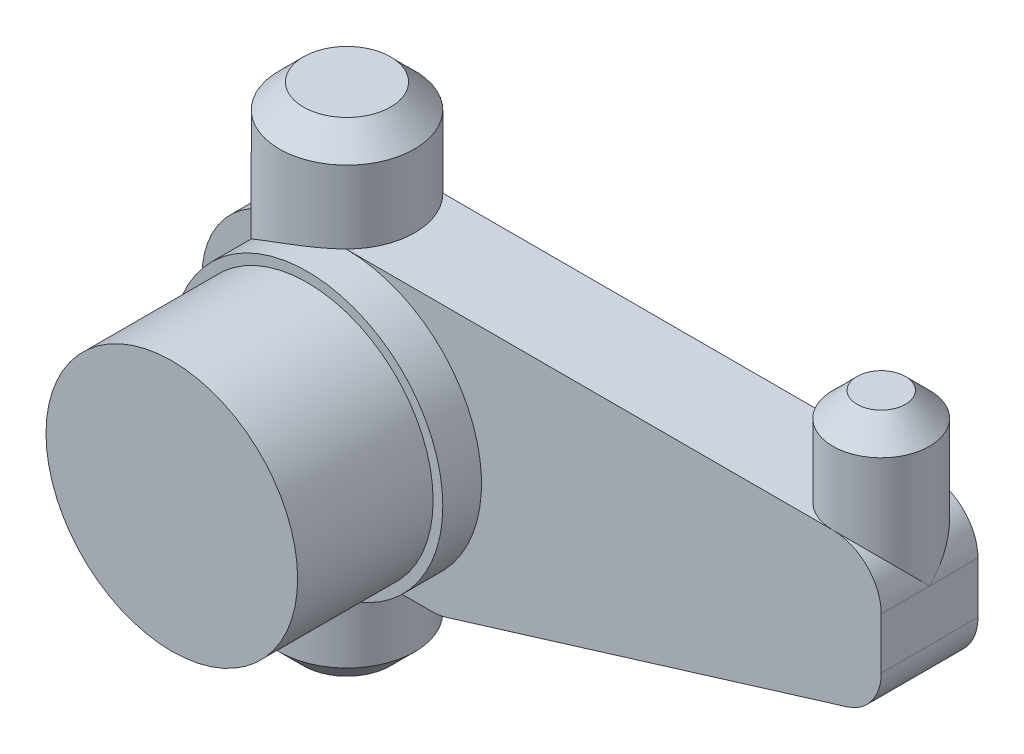
SolidWorks part; units mm, degrees
material "Alloy Steel (SS)"
ref_plane "Front Plane" through (0, 0, 0) normal (0, 0, 1) x (1, 0, 0)
ref_plane "Top Plane" through (0, 0, 0) normal (0, 1, 0) x (1, 0, 0)
ref_plane "Right Plane" through (0, 0, 0) normal (1, 0, 0) x (0, 0, -1)
sketch "Sketch1" plane through (0, 0, 0) normal (0, 0, 1) x (1, 0, 0)
  line L0 (-58.8182, 21.5635) -> (11.382, 21.5635)
  line L1 (11.382, 21.5635) -> (11.382, 7.5635)
  line L2 (-34.2829, -6.4365) -> (-58.8182, -6.4365)
  line L3 (-58.8182, -6.4365) -> (-58.8182, 21.5635)
  line L4 (-34.2829, -6.4365) -> (11.382, 7.5635)
extrude "Boss-Extrude1" add sketch "Sketch1" along normal blind 10
fillet "Fillet1" radius 10 2 edges at (-58.8182, -6.4365, 5) (-58.8182, 21.5635, 5)
fillet "Fillet2" radius 5 3 edges at (11.382, 21.5635, 5) (11.382, 7.5635, 5) (-34.2829, -6.4365, 5)
sketch "Sketch2" plane through (0, 21.5635, 0) normal (0, 1, 0) x (1, 0, 0)
  line L0 (-48.8182, 0) -> (-48.8182, -10) construction
  circle A0 centre (-48.8182, -5) radius 7
extrude "Boss-Extrude2" add sketch "Sketch2" along normal blind 10 and the other way blind 40
sketch "Sketch3" plane through (0, 21.5635, 0) normal (0, 1, 0) x (1, 0, 0)
  line L0 (6.382, -10) -> (6.382, 0) construction
  circle A0 centre (6.382, -5) radius 5
extrude "Boss-Extrude3" add sketch "Sketch3" along normal blind 10 and the other way up to vertex
chamfer "Chamfer1" distance 2.5 angle 45 3 edges at (-48.8182, -18.4365, 12) (6.382, 31.5635, 10) (-48.8182, 31.5635, 12)
sketch "Sketch4" plane through (0, 0, 10) normal (0, 0, 1) x (1, 0, 0)
  line L0 (-43.9192, -6.4365) -> (-43.9192, 21.5635)
  circle A0 centre (-43.9192, 7.5635) radius 13
extrude "Boss-Extrude4" add sketch "Sketch4" along normal blind 18 and the other way blind 10
sketch "Sketch5" plane through (0, 0, 10) normal (0, 0, 1) x (1, 0, 0)
  circle A0 centre (-43.9192, 7.5635) radius 14
extrude "Boss-Extrude5" add sketch "Sketch5" along normal blind 4
